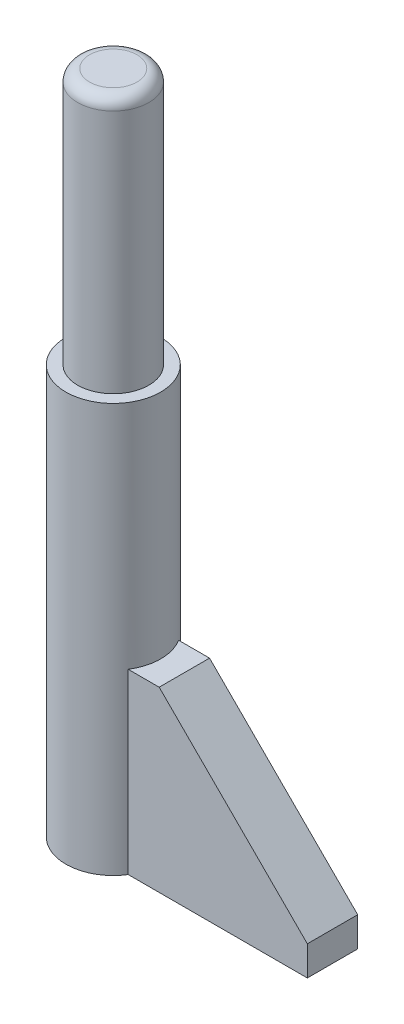
SolidWorks part; units mm, degrees
ref_plane "Front Plane" through (0, 0, 0) normal (0, 0, 1) x (1, 0, 0)
ref_plane "Top Plane" through (0, 0, 0) normal (0, 1, 0) x (1, 0, 0)
ref_plane "Right Plane" through (0, 0, 0) normal (1, 0, 0) x (0, 0, -1)
sketch "Sketch1" plane through (0, 0, 0) normal (0, 1, 0) x (1, 0, 0)
  circle A0 centre (0, 0) radius 2.032
  dimension "D1" = 4.064
extrude "Boss-Extrude1" add sketch "Sketch1" along normal blind 17.526
sketch "Sketch2" plane through (0, 0, 0) normal (0, -1, 0) x (1, 0, 0)
  line L0 (0, 0) -> (4.699, 0) construction
  line L2 (9.398, -1.0795) -> (0, -1.0795)
  line L3 (9.398, -1.0795) -> (9.398, 1.0795)
  line L4 (9.398, 1.0795) -> (0, 1.0795)
  line L5 (0, -1.0795) -> (0, 1.0795)
  line L6 (9.398, -1.0795) -> (0, 1.0795) construction
  line L7 (9.398, 1.0795) -> (0, -1.0795) construction
  dimension "D1" = 2.159
  dimension "D2" = 9.398
extrude "Boss-Extrude2" add sketch "Sketch2" against normal blind 7.62
chamfer "Chamfer1" distance 6.35 angle 45 1 edges at (9.398, 7.62, 0)
sketch "Sketch3" plane through (0, 17.526, 0) normal (0, 1, 0) x (1, 0, 0)
  circle A1 centre (0, 0) radius 1.524
  dimension "D1" = 3.048
extrude "Boss-Extrude3" add sketch "Sketch3" along normal blind 11
fillet "Fillet1" radius 0.508 1 edges at (0, 28.526, 1.524)
